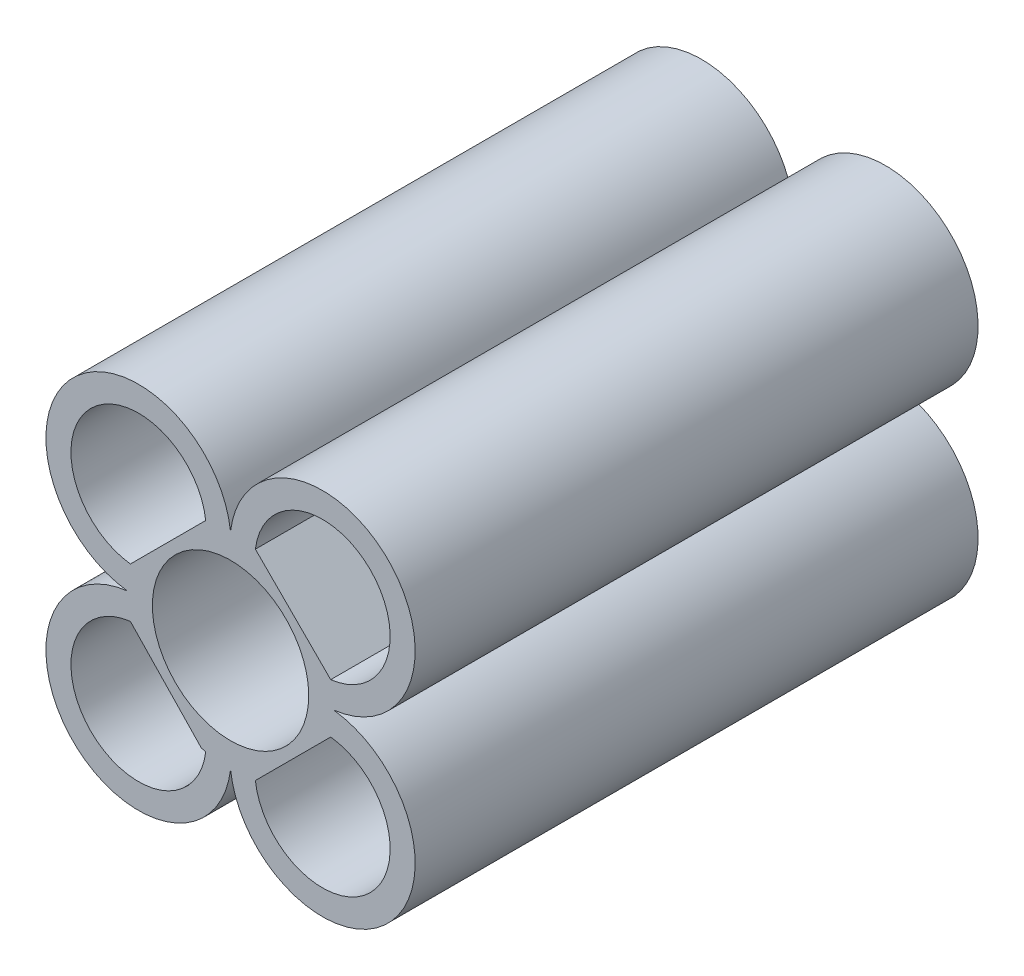
SolidWorks part; units mm, degrees
ref_plane "Front Plane" through (0, 0, 0) normal (0, 0, 1) x (1, 0, 0)
ref_plane "Top Plane" through (0, 0, 0) normal (0, 1, 0) x (1, 0, 0)
ref_plane "Right Plane" through (0, 0, 0) normal (1, 0, 0) x (0, 0, -1)
sketch "Sketch1" plane through (0, 0, 0) normal (0, 0, 1) x (1, 0, 0)
  line L0 (0, -62.5) -> (0, 219.8139) construction
  line L1 (-82.5, 0) -> (82.5, 0) construction
  line L2 (80.0758, 19.8525) -> (19.8525, 80.0758)
  line L3 (-19.8525, 80.0758) -> (-80.0758, 19.8525)
  line L4 (-80.0758, -19.8525) -> (-20.2045, -82.5)
  line L5 (19.8525, -80.0758) -> (80.0758, -19.8525)
  circle A0 centre (0, 0) radius 62.5
  arc A2 (-82.5, 0) -> (0, 82.5) centre (-73.522, 73.522) cw
  arc A3 (-80.0758, 19.8525) -> (-19.8525, 80.0758) centre (-73.522, 73.522) cw
  arc A4 (-80.0758, -19.8525) -> (-19.8525, -80.0758) centre (-73.522, -73.522) ccw
  arc A5 (-82.5, 0) -> (0, -82.5) centre (-73.522, -73.522) ccw
  arc A6 (80.0758, -19.8525) -> (19.8525, -80.0758) centre (73.522, -73.522) cw
  arc A7 (82.5, 0) -> (0, -82.5) centre (73.522, -73.522) cw
  arc A8 (80.0758, 19.8525) -> (19.8525, 80.0758) centre (73.522, 73.522) ccw
  arc A9 (82.5, 0) -> (0, 82.5) centre (73.522, 73.522) ccw
  arc A11 (-23.4592, -79.0943) -> (-19.8525, -80.0758) centre (0, 0) ccw
extrude "Boss-Extrude1" add sketch "Sketch1" along normal blind 450
scale "Scale1" scale about centroid uniform scaling yes scale factor 2
